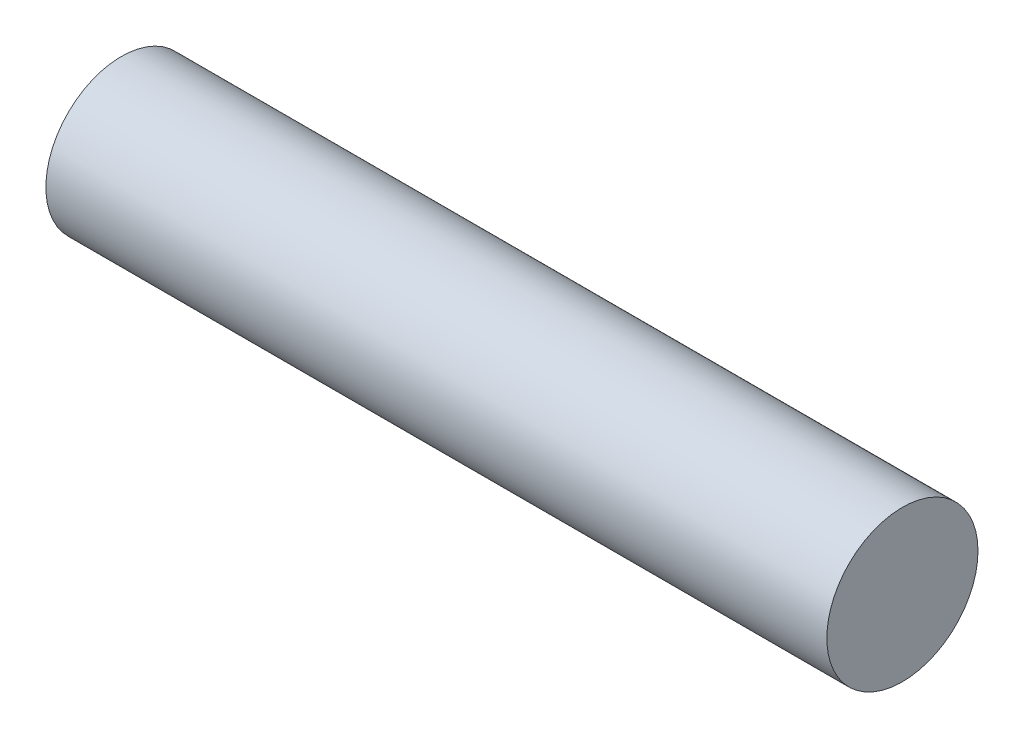
SolidWorks part; units mm, degrees
ref_plane "Front Plane" through (0, 0, 0) normal (0, 0, 1) x (1, 0, 0)
ref_plane "Top Plane" through (0, 0, 0) normal (0, 1, 0) x (1, 0, 0)
ref_plane "Right Plane" through (0, 0, 0) normal (1, 0, 0) x (0, 0, -1)
sketch "Sketch1" plane through (0, 0, 0) normal (1, 0, 0) x (0, 0, -1)
  circle A0 centre (0, 0) radius 6
  dimension "D1" = 12
extrude "Boss-Extrude1" add sketch "Sketch1" along normal blind 62
